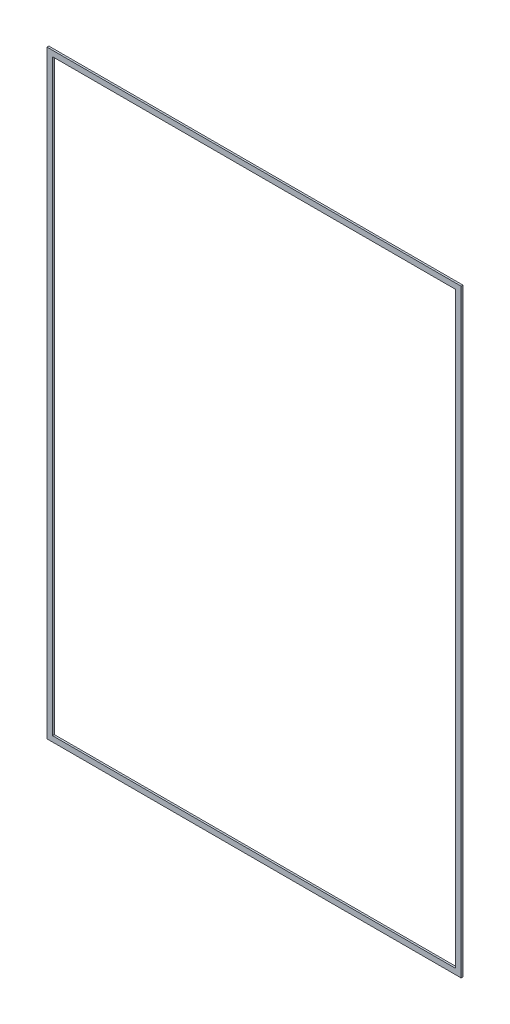
SolidWorks part; units mm, degrees
ref_plane "Front Plane" through (0, 0, 0) normal (0, 0, 1) x (1, 0, 0)
ref_plane "Top Plane" through (0, 0, 0) normal (0, 1, 0) x (1, 0, 0)
ref_plane "Right Plane" through (0, 0, 0) normal (1, 0, 0) x (0, 0, -1)
sketch "Sketch1" plane through (0, 0, 0) normal (0, 0, 1) x (1, 0, 0)
  line L1 (0, 0) -> (224, 0)
  line L2 (0, 0) -> (0, 324)
  line L3 (0, 324) -> (224, 324)
  line L4 (224, 0) -> (224, 324)
  line L5 (3, 3) -> (221, 3)
  line L6 (3, 3) -> (3, 321)
  line L7 (3, 321) -> (221, 321)
  line L8 (221, 3) -> (221, 321)
  dimension "D1" = 3
  dimension "D2" = 221
  dimension "D3" = 224
  dimension "D4" = 3
  dimension "D5" = 321
  dimension "D6" = 324
extrude "Profile" add sketch "Sketch1" along normal blind 1
equation "\"Profile_Depth\" = 1mm"
equation "\"D1@Profile\" = \"Profile_Depth\""
equation "\"EnvelopeWidth\" = 224mm"
equation "\"EnvelopeHeight\" = 324mm"
